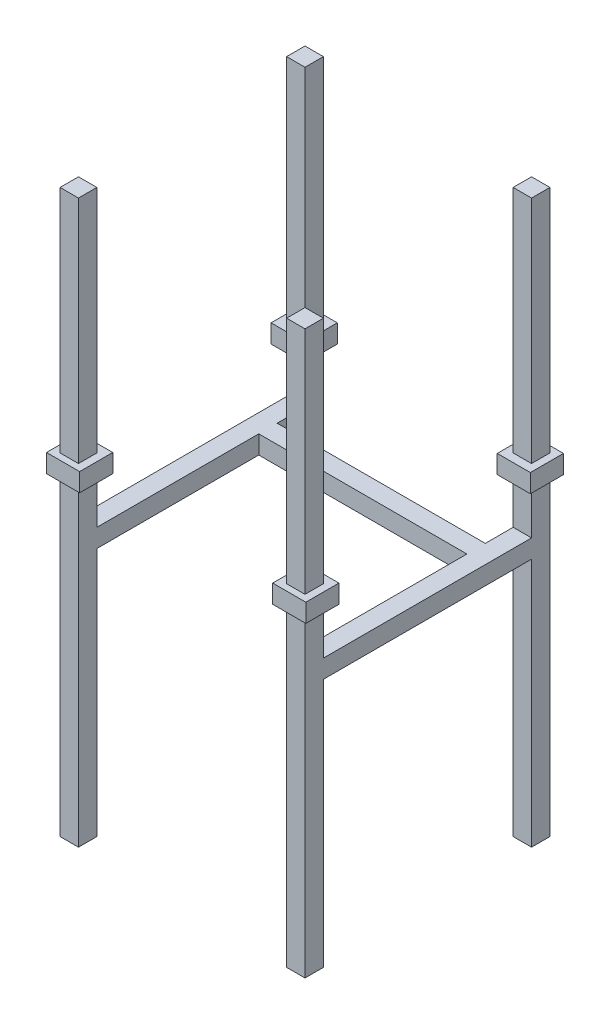
SolidWorks part; units mm, degrees
ref_plane "Alzado" through (0, 0, 0) normal (0, 0, 1) x (1, 0, 0)
ref_plane "Planta" through (0, 0, 0) normal (0, 1, 0) x (1, 0, 0)
ref_plane "Vista lateral" through (0, 0, 0) normal (1, 0, 0) x (0, 0, -1)
sketch "Croquis1" plane through (0, 0, 0) normal (0, 1, 0) x (1, 0, 0)
  line L0 (0, 400) -> (0, -400) construction
  line L1 (-282.8427, 282.8427) -> (282.8427, 282.8427) construction
  line L2 (-282.8427, 282.8427) -> (-282.8427, -282.8427) construction
  line L3 (-282.8427, -282.8427) -> (282.8427, -282.8427) construction
  line L4 (282.8427, 282.8427) -> (282.8427, -282.8427) construction
  line L5 (-282.8427, 282.8427) -> (282.8427, -282.8427) construction
  line L6 (-282.8427, -282.8427) -> (282.8427, 282.8427) construction
  line L7 (-282.8427, 282.8427) -> (-332.8427, 282.8427)
  line L8 (-282.8427, 282.8427) -> (-282.8427, 332.8427)
  line L9 (-282.8427, 332.8427) -> (-332.8427, 332.8427)
  line L10 (-332.8427, 282.8427) -> (-332.8427, 332.8427)
  line L11 (332.8427, 282.8427) -> (332.8427, 332.8427)
  line L12 (282.8427, 332.8427) -> (332.8427, 332.8427)
  line L13 (282.8427, 282.8427) -> (282.8427, 332.8427)
  line L14 (282.8427, 282.8427) -> (332.8427, 282.8427)
  line L15 (-400, 0) -> (400, 0) construction
  line L16 (-332.8427, -282.8427) -> (-332.8427, -332.8427)
  line L17 (-282.8427, -332.8427) -> (-332.8427, -332.8427)
  line L18 (-282.8427, -282.8427) -> (-282.8427, -332.8427)
  line L19 (-282.8427, -282.8427) -> (-332.8427, -282.8427)
  line L20 (282.8427, -282.8427) -> (332.8427, -282.8427)
  line L21 (282.8427, -282.8427) -> (282.8427, -332.8427)
  line L22 (282.8427, -332.8427) -> (332.8427, -332.8427)
  line L23 (332.8427, -282.8427) -> (332.8427, -332.8427)
  circle A0 centre (0, 0) radius 400 construction
  dimension "D1" = 800
  dimension "D2" = 50
  dimension "D3" = 50
extrude "Saliente-Extruir1" add sketch "Croquis1" against normal blind 625
sketch "Croquis2" plane through (0, -625, 0) normal (0, -1, 0) x (1, 0, 0)
  line L0 (0, 305.1451) -> (0, -307.8427) construction
  line L1 (-352.361, 350.1451) -> (-262.361, 350.1451)
  line L2 (-352.361, 350.1451) -> (-352.361, 260.1451)
  line L3 (-352.361, 260.1451) -> (-262.361, 260.1451)
  line L4 (-262.361, 350.1451) -> (-262.361, 260.1451)
  line L5 (-352.361, 350.1451) -> (-262.361, 260.1451) construction
  line L6 (-352.361, 260.1451) -> (-262.361, 350.1451) construction
  line L7 (-307.361, 0) -> (310.4962, 0) construction
  line L8 (352.361, 260.1451) -> (262.361, 350.1451) construction
  line L9 (352.361, 350.1451) -> (262.361, 260.1451) construction
  line L10 (262.361, 350.1451) -> (262.361, 260.1451)
  line L11 (352.361, 260.1451) -> (262.361, 260.1451)
  line L12 (352.361, 350.1451) -> (352.361, 260.1451)
  line L13 (352.361, 350.1451) -> (262.361, 350.1451)
  line L14 (352.361, -350.1451) -> (262.361, -260.1451) construction
  line L15 (352.361, -260.1451) -> (262.361, -350.1451) construction
  line L16 (352.361, -350.1451) -> (262.361, -350.1451)
  line L17 (352.361, -350.1451) -> (352.361, -260.1451)
  line L18 (352.361, -260.1451) -> (262.361, -260.1451)
  line L19 (262.361, -350.1451) -> (262.361, -260.1451)
  line L20 (-352.361, -260.1451) -> (-262.361, -350.1451) construction
  line L21 (-352.361, -350.1451) -> (-262.361, -260.1451) construction
  line L22 (-262.361, -350.1451) -> (-262.361, -260.1451)
  line L23 (-352.361, -260.1451) -> (-262.361, -260.1451)
  line L24 (-352.361, -350.1451) -> (-352.361, -260.1451)
  line L25 (-352.361, -350.1451) -> (-262.361, -350.1451)
  point P0 (-307.361, 305.1451)
  point P14 (307.361, 305.1451)
  point P19 (307.361, -305.1451)
  point P24 (-307.361, -305.1451)
  dimension "D1" = 90
  dimension "D2" = 90
extrude "Saliente-Extruir2" add sketch "Croquis2" along normal blind 50
sketch "Croquis4" plane through (0, -675, 0) normal (0, -1, 0) x (1, 0, 0)
  line L0 (0, -282.8427) -> (0, 282.8427) construction
  line L1 (-282.8427, 282.8427) -> (-332.8427, 282.8427)
  line L2 (-282.8427, 282.8427) -> (-282.8427, 332.8427)
  line L3 (-282.8427, 332.8427) -> (-332.8427, 332.8427)
  line L4 (-332.8427, 282.8427) -> (-332.8427, 332.8427)
  line L5 (-275.9995, 0) -> (282.8427, 0) construction
  line L6 (-332.8427, -282.8427) -> (-332.8427, -332.8427)
  line L7 (-282.8427, -332.8427) -> (-332.8427, -332.8427)
  line L8 (-282.8427, -282.8427) -> (-282.8427, -332.8427)
  line L9 (-282.8427, -282.8427) -> (-332.8427, -282.8427)
  line L10 (332.8427, 282.8427) -> (332.8427, 332.8427)
  line L11 (282.8427, 332.8427) -> (332.8427, 332.8427)
  line L12 (282.8427, 282.8427) -> (282.8427, 332.8427)
  line L13 (282.8427, 282.8427) -> (332.8427, 282.8427)
  line L14 (282.8427, -282.8427) -> (332.8427, -282.8427)
  line L15 (282.8427, -282.8427) -> (282.8427, -332.8427)
  line L16 (282.8427, -332.8427) -> (332.8427, -332.8427)
  line L17 (332.8427, -282.8427) -> (332.8427, -332.8427)
extrude "Saliente-Extruir3" add sketch "Croquis4" along normal blind 853
ref_plane "Plano1" through (0, -800, 0) normal (0, 1, 0) x (1, 0, 0)
sketch "Croquis6" plane through (0, -800, 0) normal (0, 1, 0) x (1, 0, 0)
  line L0 (282.8427, 332.8427) -> (282.8427, 282.8427) construction
  line L2 (332.8427, 282.8427) -> (332.8427, -332.8427)
  line L4 (-332.8427, 282.8427) -> (-332.8427, -332.8427)
  line L6 (282.8427, 282.8427) -> (282.8427, 207.1573)
  line L8 (-282.8427, 282.8427) -> (-282.8427, 207.1573)
  line L9 (282.8427, 157.1573) -> (282.8427, -282.8427)
  line L10 (-282.8427, 157.1573) -> (-282.8427, -282.8427)
  line L11 (-282.8427, 207.1573) -> (282.8427, 207.1573)
  line L13 (-282.8427, 157.1573) -> (282.8427, 157.1573)
  line L15 (-282.8427, -282.8427) -> (-282.8427, -332.8427)
  line L16 (-282.8427, -332.8427) -> (-332.8427, -332.8427)
  line L17 (282.8427, -282.8427) -> (282.8427, -332.8427)
  line L18 (282.8427, -332.8427) -> (332.8427, -332.8427)
  line L19 (-282.8427, 282.8427) -> (-332.8427, 282.8427)
  line L20 (282.8427, 282.8427) -> (332.8427, 282.8427)
  dimension "D1" = 50
  dimension "D2" = 490
extrude "Saliente-Extruir4" add sketch "Croquis6" against normal blind 50
